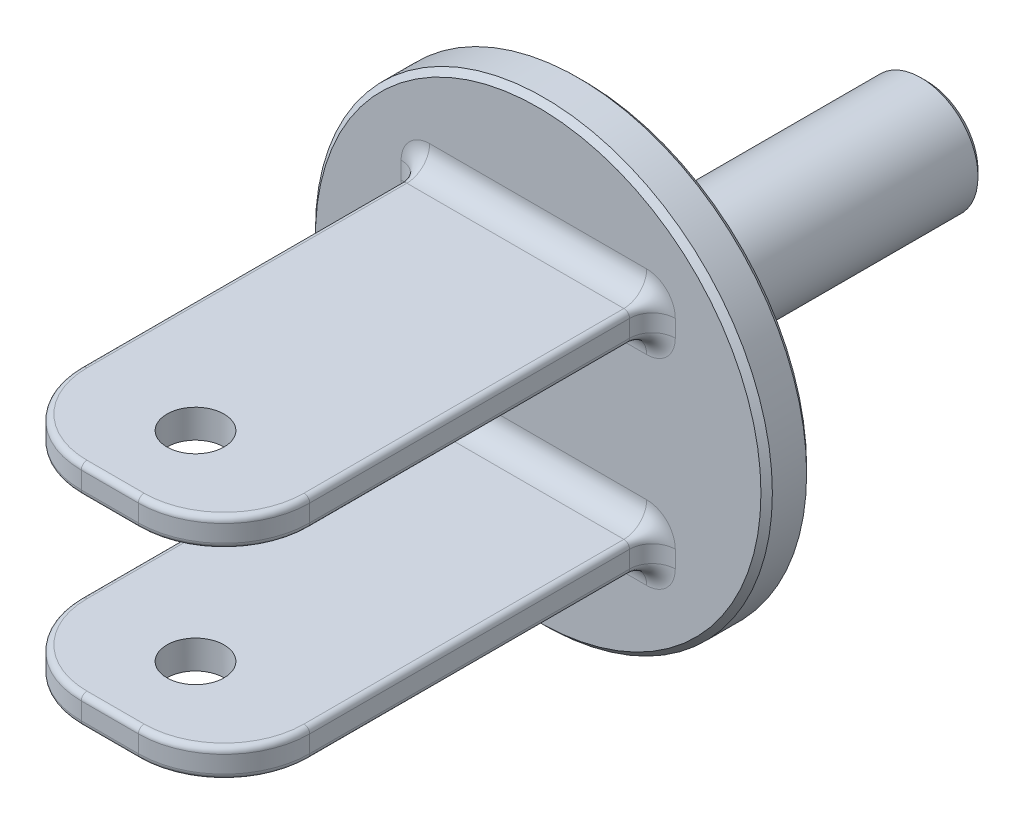
SolidWorks part; units mm, degrees
ref_plane "Front Plane" through (0, 0, 0) normal (0, 0, 1) x (1, 0, 0)
ref_plane "Top Plane" through (0, 0, 0) normal (0, 1, 0) x (1, 0, 0)
ref_plane "Right Plane" through (0, 0, 0) normal (1, 0, 0) x (0, 0, -1)
sketch "Sketch2" plane through (0, 0, 0) normal (0, 0, 1) x (1, 0, 0)
  circle A0 centre (0, 0) radius 40
  dimension "D1" = 80
extrude "Boss-Extrude1" add sketch "Sketch2" along normal blind 8 contours A0
sketch "Sketch3" plane through (0, 0, 8) normal (0, 0, 1) x (1, 0, 0)
  line L0 (0, 0) -> (0, 40) construction
  line L2 (20, 20) -> (-20, 20)
  line L3 (20, 20) -> (20, 15)
  line L4 (20, 15) -> (-20, 15)
  line L5 (-20, 20) -> (-20, 15)
  line L6 (20, 20) -> (-20, 15) construction
  line L7 (20, 15) -> (-20, 20) construction
  circle A0 centre (0, 0) radius 40 construction
  point P5 (0, 17.5)
  dimension "D1" = 15
  dimension "D2" = 40
  dimension "D3" = 5
extrude "Boss-Extrude2" add sketch "Sketch3" along normal blind 75
fillet "Fillet1" radius 15 2 edges at (20, 17.5, 83) (-20, 17.5, 83)
fillet "Fillet3" radius 1 10 edges at (0, 20, 83) (15.6066, 20, 78.6066) (20, 20, 38) (-15.6066, 20, 78.6066) (-20, 20, 38) (0, 15, 83) (15.6066, 15, 78.6066) (20, 15, 38) (-15.6066, 15, 78.6066) (-20, 15, 38)
fillet "Fillet5" radius 4 8 edges at (-19.7071, 15.2929, 8) (-20, 17.5, 8) (-19.7071, 19.7071, 8) (19.7071, 19.7071, 8) (20, 17.5, 8) (19.7071, 15.2929, 8) (0, 20, 8) (0, 15, 8)
mirror "Mirror3" about plane through (0, 0, 0) normal (0, 1, 0) of "Fillet5", "Fillet3", "Fillet1", "Boss-Extrude2"
sketch "Sketch6" plane through (0, 0, 0) normal (0, 1, 0) x (1, 0, 0)
  line L0 (0, 0) -> (0, -83.0142) construction
  line L1 (-5, -83) -> (5, -83) construction
  circle A0 centre (0, -68) radius 5
  dimension "D1" = 10
  dimension "D2" = 15
extrude "Cut-Extrude5" cut sketch "Sketch6" along normal up to surface and the other way up to next contours A0 up to face at (0, 20, 54.9665)
sketch "Sketch12" plane through (0, 0, 0) normal (0, 0, 1) x (1, 0, 0)
  circle A0 centre (0, 0) radius 10
  circle A1 centre (0, 0) radius 7.5
  dimension "D1" = 20
  dimension "D2" = 15
extrude "Boss-Extrude6" add sketch "Sketch12" against normal blind 60
chamfer "Chamfer2" distance 1 angle 45 3 edges at (40, 0, 8) (10, 0, -60) (40, 0, 0)
